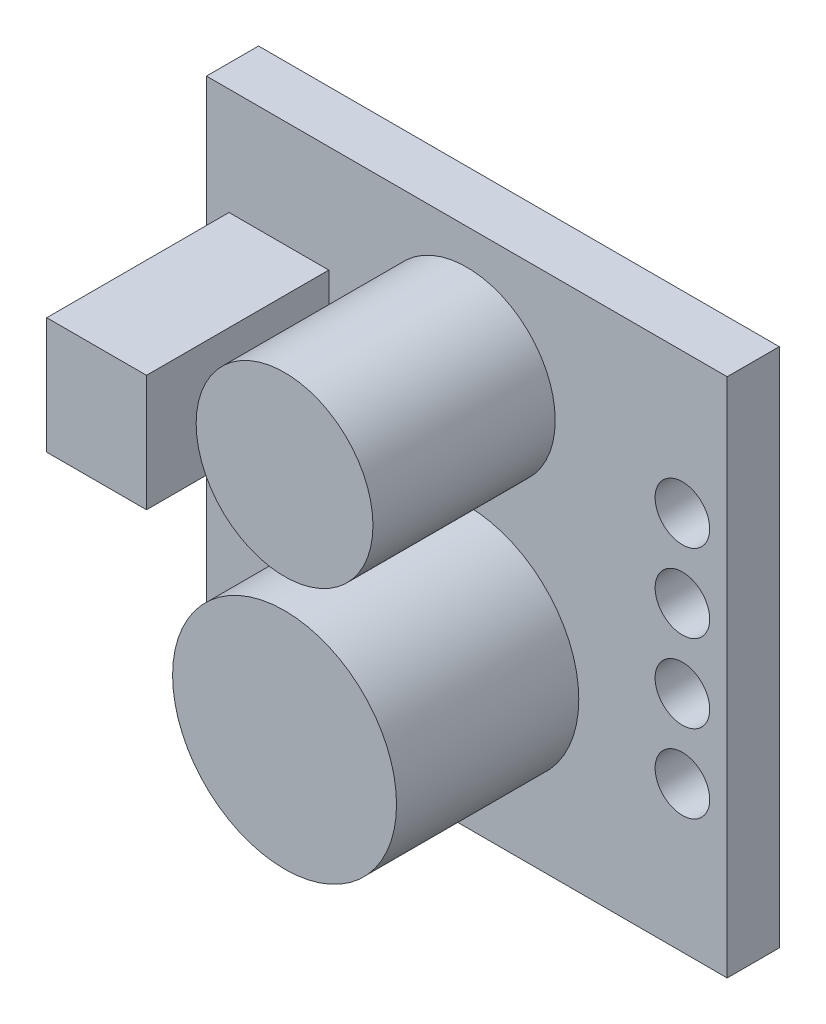
SolidWorks part; units mm, degrees
ref_plane "Alzado" through (0, 0, 0) normal (0, 0, 1) x (1, 0, 0)
ref_plane "Planta" through (0, 0, 0) normal (0, 1, 0) x (1, 0, 0)
ref_plane "Vista lateral" through (0, 0, 0) normal (1, 0, 0) x (0, 0, -1)
sketch "Croquis1" plane through (0, 0, 0) normal (0, 0, 1) x (1, 0, 0)
  line L1 (-10, -10) -> (10, -10)
  line L2 (-10, -10) -> (-10, 10)
  line L3 (-10, 10) -> (10, 10)
  line L4 (10, -10) -> (10, 10)
  line L5 (-10, -10) -> (10, 10) construction
  line L6 (-10, 10) -> (10, -10) construction
  point P0 (0, 0)
  dimension "D1" = 20
  dimension "D2" = 20
extrude "Saliente-Extruir1" add sketch "Croquis1" along normal blind 2
sketch "Croquis2" plane through (0, 0, 2) normal (0, 0, 1) x (1, 0, 0)
  line L1 (-9.1339, 1.4217) -> (-5.3018, 1.4217)
  line L2 (-9.1339, 1.4217) -> (-9.1339, 5.8959)
  line L3 (-9.1339, 5.8959) -> (-5.3018, 5.8959)
  line L4 (-5.3018, 1.4217) -> (-5.3018, 5.8959)
  line L5 (-9.1339, 1.4217) -> (-5.3018, 5.8959) construction
  line L6 (-9.1339, 5.8959) -> (-5.3018, 1.4217) construction
  circle A0 centre (0, 5.247) radius 3.3953
  circle A1 centre (0, -3.578) radius 4.3006
  point P4 (-7.2179, 3.6588)
extrude "Saliente-Extruir2" add sketch "Croquis2" along normal blind 7
sketch "Croquis3" plane through (0, 0, 2) normal (0, 0, 1) x (1, 0, 0)
  circle A0 centre (8.2801, 4.598) radius 1.0489
  circle A1 centre (8.2801, 1.598) radius 1.0489
  circle A2 centre (8.2801, -1.402) radius 1.0489
  circle A3 centre (8.2801, -4.402) radius 1.0489
  dimension "D1" = 4
extrude "Cortar-Extruir1" cut sketch "Croquis3" against normal up to vertex (2 mm away)
